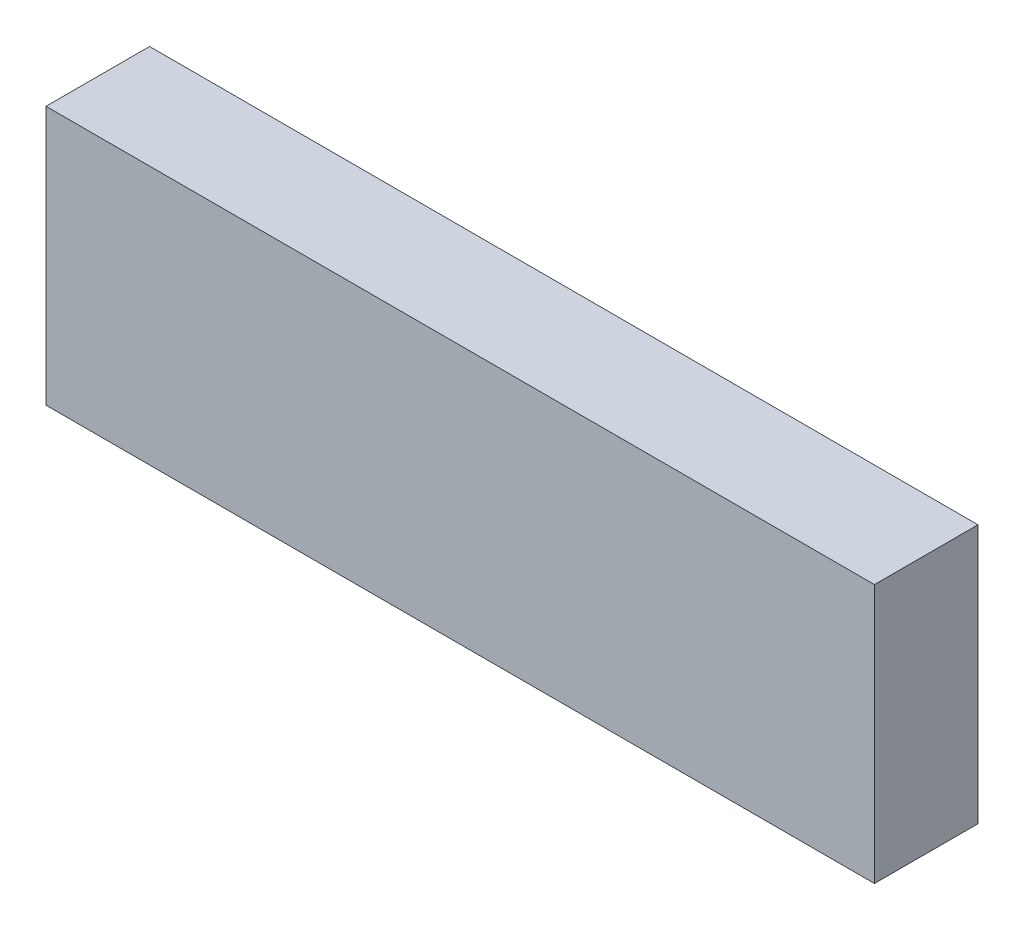
SolidWorks part; units mm, degrees
ref_plane "Alzado" through (0, 0, 0) normal (0, 0, 1) x (1, 0, 0)
ref_plane "Planta" through (0, 0, 0) normal (0, 1, 0) x (1, 0, 0)
ref_plane "Vista lateral" through (0, 0, 0) normal (1, 0, 0) x (0, 0, -1)
sketch "Croquis1" plane through (0, 0, 0) normal (0, 0, 1) x (1, 0, 0)
  line L1 (-40, -12.5) -> (40, -12.5)
  line L2 (-40, -12.5) -> (-40, 12.5)
  line L3 (-40, 12.5) -> (40, 12.5)
  line L4 (40, -12.5) -> (40, 12.5)
  line L5 (-40, -12.5) -> (40, 12.5) construction
  line L6 (-40, 12.5) -> (40, -12.5) construction
  point P0 (0, 0)
  dimension "D1" = 80
  dimension "D2" = 25
extrude "Saliente-Extruir1" add sketch "Croquis1" along normal blind 10
